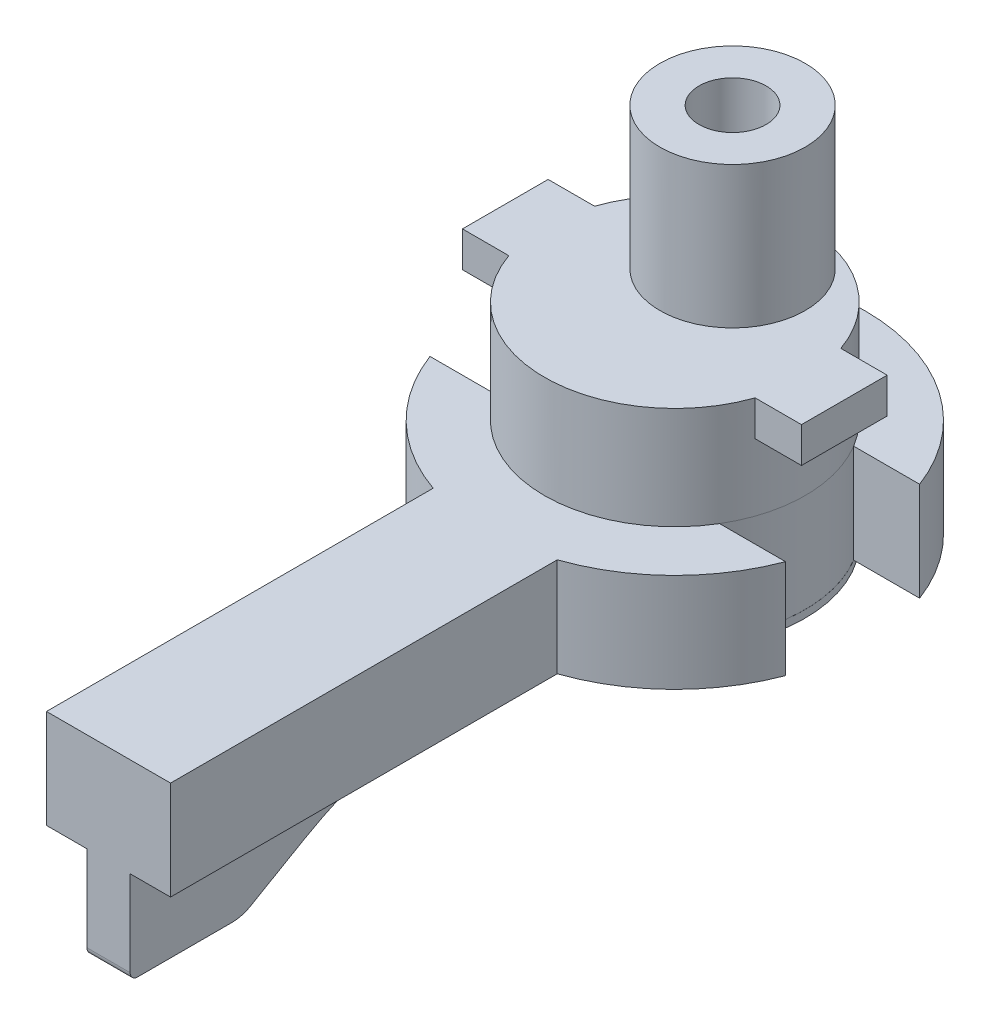
SolidWorks part; units mm, degrees
ref_plane "Alzado" through (0, 0, 0) normal (0, 0, 1) x (1, 0, 0)
ref_plane "Planta" through (0, 0, 0) normal (0, 1, 0) x (1, 0, 0)
ref_plane "Vista lateral" through (0, 0, 0) normal (1, 0, 0) x (0, 0, -1)
sketch "Croquis1" plane through (0, 0, 0) normal (0, 1, 0) x (1, 0, 0)
  circle A0 centre (0, 0) radius 5.1
  dimension "D1" = 10.2
extrude "Saliente-Extruir2" add sketch "Croquis1" along normal blind 2.85
sketch "Croquis4" plane through (0, 2.85, 0) normal (0, 1, 0) x (1, 0, 0)
  circle A0 centre (0, 0) radius 3.5
  dimension "D1" = 7
extrude "Saliente-Extruir3" add sketch "Croquis4" along normal blind 2.75
sketch "Croquis5" plane through (0, 5.6, 0) normal (0, 1, 0) x (1, 0, 0)
  line L0 (0, 0) -> (0, 4.2752) construction
  circle A0 centre (0, 1.55) radius 1.95
  circle A1 centre (0, 0) radius 3.5 construction
  dimension "D1" = 3.9
extrude "Saliente-Extruir4" add sketch "Croquis5" along normal blind 3.8
sketch "Croquis7" plane through (0, 0, 0) normal (0, 0, 1) x (1, 0, 0)
  line L0 (0, 2.85) -> (1.665, 2.85)
  line L1 (5.1, 2.85) -> (-5.1, 2.85) construction
  line L2 (0, 2.85) -> (-1.665, 2.85)
  line L3 (-1.665, 2.85) -> (-1.665, -2.3)
  line L4 (1.665, 2.85) -> (1.665, -2.3)
  line L5 (1.665, -2.3) -> (-1.665, -2.3)
  dimension "D1" = 1.665
  dimension "D2" = 5.15
extrude "Saliente-Extruir5" add sketch "Croquis7" along normal blind 15.2
sketch "Croquis8" plane through (0, 0, 15.2) normal (0, 0, 1) x (1, 0, 0)
  line L2 (-1.665, 2.85) -> (1.665, 2.85)
  line L7 (-1.665, -2.3) -> (1.665, -2.3) construction
  line L8 (0.58, -2.3) -> (-0.58, -2.3)
  line L11 (0, 0) -> (-0.58, 0) construction
  line L12 (0, 0) -> (0.58, 0) construction
  line L13 (-0.58, -2.3) -> (-1.665, -2.3)
  line L15 (0.58, -2.3) -> (1.665, -2.3)
  line L17 (-1.665, 2.85) -> (-1.665, 0)
  line L18 (-1.665, 2.85) -> (-1.665, -2.3) construction
  line L19 (-1.665, 0) -> (-0.58, 0)
  line L20 (-0.58, 0) -> (-0.58, -2.3)
  line L21 (0.58, -2.3) -> (0.58, 0)
  line L22 (0.58, 0) -> (1.665, 0)
  line L23 (1.665, 0) -> (1.665, 2.85)
  line M12 (-1.665, 2.85) -> (-1.665, -2.3)
  line M13 (-1.665, -2.3) -> (1.665, -2.3)
  line M14 (1.665, -2.3) -> (1.665, 2.85)
  dimension "D2" = 0.58
sketch "Croquis11" plane through (1.665, 0, 0) normal (1, 0, 0) x (0, 0, -1)
  line L0 (0, -2.3) -> (0, 0)
  line L1 (0, 0) -> (-4.8206, 0)
  line L2 (0, 0) -> (-4.8206, 0) construction
  line L3 (-12.2, -2.3) -> (-7.9598, 0.1481)
  line L4 (-15.2, -2.3) -> (0, -2.3) construction
  line L5 (-12.2, -2.3) -> (-0.2175, -2.3)
  line L7 (-4.8206, 0) -> (-8.2163, 0)
  line L8 (-12.2, -2.3) -> (0, -2.3)
  line L9 (0, 0) -> (-8.2163, 0)
  line M4 (0, 0) -> (-4.8206, 0)
  line M8 (-15.2, -2.3) -> (0, -2.3)
  line M9 (0, -2.3) -> (0, 0)
  dimension "D2" = 30
extrude "Cortar-Extruir4" cut sketch "Croquis11" against normal up to next contours L7 L3 M4 M8 M9
extrude "Cortar-Extruir6" cut sketch "Croquis8" against normal blind 10.2 contours L20 L19 M12 M13 | L22 L21 M13 M14
fillet "Redondeo1" radius 1 1 edges at (0, -2.3, 12.2)
fillet "Redondeo2" radius 10 1 edges at (0, 0, 8.2163)
sketch "Croquis12" plane through (0, 0, 0) normal (0, -1, 0) x (1, 0, 0)
  line L0 (-1.665, 15.2) -> (-0.58, 15.2)
  line L1 (-0.58, 15.2) -> (-0.58, 5.5368)
  line L2 (-0.58, 5.5368) -> (-0.58, 3.4516)
  line L3 (0.58, 15.2) -> (0.58, 3.4516)
  line L4 (-0.58, 15.2) -> (0.58, 15.2)
  arc A0 (-0.58, 3.4516) -> (0.58, 3.4516) centre (0, 0) ccw
  line M2 (0.58, 15.2) -> (0.58, 5.5368)
  line M4 (-0.58, 5.5368) -> (-0.58, 15.2)
  line M5 (-0.58, 15.2) -> (-1.665, 15.2)
  line M6 (-1.665, 15.2) -> (-1.665, 4.8206)
  arc M7 (-1.665, 4.8206) -> (1.665, 4.8206) centre (0, 0) ccw
  line M8 (1.665, 4.8206) -> (1.665, 15.2)
  line M9 (1.665, 15.2) -> (0.58, 15.2)
  dimension "D1" = 7
extrude "Cortar-Extruir7" cut sketch "Croquis12" against normal blind 0.2 contours A0 L2 L3 M4 M5 M6 M7 M8 M9 M2
sketch "Croquis13" plane through (0, 0, 0) normal (0, -1, 0) x (1, 0, 0)
  circle A0 centre (0, 0) radius 2.5
  dimension "D1" = 5
extrude "Cortar-Extruir8" cut sketch "Croquis13" against normal blind 3.2
sketch "Croquis14" plane through (0, 9.4, 0) normal (0, 1, 0) x (1, 0, 0)
  circle A0 centre (0, 1.55) radius 0.9
  dimension "D1" = 1.8
extrude "Cortar-Extruir9" cut sketch "Croquis14" against normal blind 3.7
sketch "Croquis15" plane through (0, 0.2, 0) normal (0, -1, 0) x (1, 0, 0)
  line L0 (0, 0) -> (0, 1.8) construction
  line L1 (0, 0) -> (0, -1.8) construction
  line L2 (-4.7718, 1.8) -> (-2.9996, 1.8)
  line L3 (-2.9996, -1.8) -> (-4.7718, -1.8)
  line L4 (4.7718, -1.8) -> (2.9996, -1.8)
  line L5 (2.9996, 1.8) -> (4.7718, 1.8)
  arc A0 (-2.9996, 1.8) -> (-2.9996, -1.8) centre (0, 0) ccw
  arc A1 (-4.7718, 1.8) -> (-4.7718, -1.8) centre (0, 0) ccw
  arc A2 (4.7718, -1.8) -> (4.7718, 1.8) centre (0, 0) ccw
  arc A3 (2.9996, -1.8) -> (2.9996, 1.8) centre (0, 0) ccw
  dimension "D1" = 1.8
extrude "Cortar-Extruir10" cut sketch "Croquis15" against normal up to surface (2.65 mm away)
fillet "Redondeo3" radius 0.2 1 edges at (0, -2.3, 15.2)
sketch "Croquis16" plane through (0, 0, 0) normal (1, 0, 0) x (0, 0, -1)
  line L0 (0, 0.2) -> (0, 5.6) construction
  line L1 (1.8, 0.2) -> (-1.8, 0.2) construction
  line L2 (3.5, 5.6) -> (-3.5, 5.6) construction
  line L3 (0, 5.6) -> (1.15, 5.6)
  line L4 (1.15, 5.6) -> (1.15, 4.65)
  line L5 (1.15, 4.65) -> (-1.15, 4.65)
  line L6 (-1.15, 4.65) -> (-1.15, 5.6)
  line L7 (-1.15, 5.6) -> (0, 5.6)
  dimension "D1" = 1.15
  dimension "D2" = 0.95
extrude "Saliente-Extruir6" add sketch "Croquis16" along normal blind 4.55 and the other way blind 4.55 contours L7 L3 L4 L5 L6
